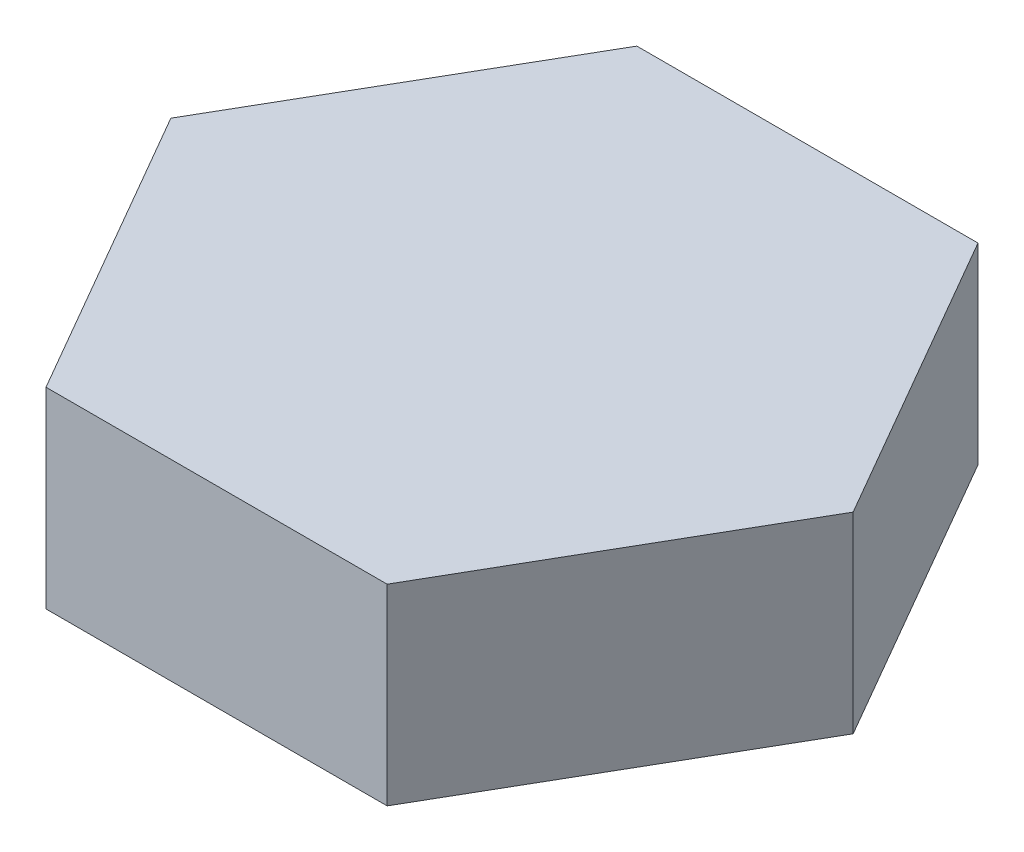
SolidWorks part; units mm, degrees
ref_plane "Front Plane" through (0, 0, 0) normal (0, 0, 1) x (1, 0, 0)
ref_plane "Top Plane" through (0, 0, 0) normal (0, 1, 0) x (1, 0, 0)
ref_plane "Right Plane" through (0, 0, 0) normal (1, 0, 0) x (0, 0, -1)
sketch "Sketch1" plane through (0, 0, 0) normal (0, 1, 0) x (1, 0, 0)
  line L0 (-58.6588, 0) -> (-29.3294, -50.8)
  line L1 (58.6588, 0) -> (29.3294, 50.8)
  line L2 (29.3294, 50.8) -> (-29.3294, 50.8)
  line L3 (-29.3294, 50.8) -> (-58.6588, 0)
  line L4 (-29.3294, -50.8) -> (29.3294, -50.8)
  line L5 (29.3294, -50.8) -> (58.6588, 0)
  circle A0 centre (0, 0) radius 50.8 construction
  dimension "D1" = 101.6
extrude "Boss-Extrude1" add sketch "Sketch1" along normal mid plane 33.02
